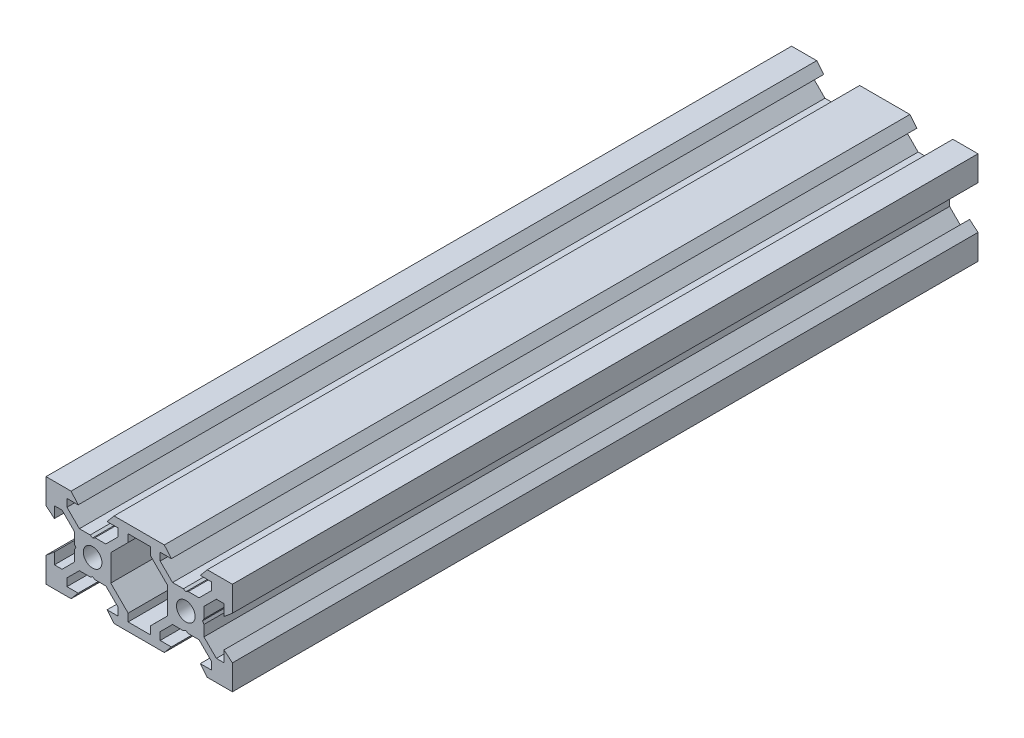
SolidWorks part; units mm, degrees
ref_plane "Front Plane" through (0, 0, 0) normal (0, 0, 1) x (1, 0, 0)
ref_plane "Top Plane" through (0, 0, 0) normal (0, 1, 0) x (1, 0, 0)
ref_plane "Right Plane" through (0, 0, 0) normal (1, 0, 0) x (0, 0, -1)
sketch "Sketch1" plane through (0, 0, 0) normal (0, 0, 1) x (1, 0, 0)
  line L0 (-5.3896, 10) -> (5.3896, 10)
  line L1 (0, 10) -> (0, 4.6104) construction
  line L2 (-6.1, -2.8393) -> (-2.3769, -6.5562)
  line L3 (5.3896, -10) -> (-5.3896, -10) construction
  line L5 (-6.1, 2.8393) -> (-6.1, -2.8393)
  line L6 (-4.5, 8.2) -> (-4.5, 6.5562)
  line L7 (2.3832, 6.5562) -> (2.3832, 8.2)
  line L9 (-6.1, 2.8393) -> (-2.3832, 6.5562)
  line L10 (-4.5, 6.5562) -> (-7.1607, 3.9)
  line L11 (-2.3832, 6.5562) -> (-2.3832, 8.2)
  line L12 (-5.3896, 10) -> (-6.9, 8.2)
  line L13 (6.1, 2.8393) -> (2.3832, 6.5562)
  line L14 (-6.9, 8.2) -> (-4.5, 8.2)
  line L15 (-16.5562, 5.5) -> (-18.2, 5.5)
  line L16 (0, 0) -> (6.1, 0) construction
  line L17 (-6.9, -8.2) -> (-4.5, -8.2)
  line L18 (-2.3769, -6.5562) -> (-2.3769, -8.2)
  line L19 (-5.3896, -10) -> (-6.9, -8.2)
  line L20 (2.3769, -6.5562) -> (2.3769, -8.2)
  line L21 (-9.4804, -3.9002) -> (-10, -3.6002)
  line L22 (-9.4804, 3.8998) -> (-10, 3.5998)
  line L23 (6.1, -2.8393) -> (2.3769, -6.5562)
  line L24 (-2.3769, -8.2) -> (2.3769, -8.2)
  line L25 (-2.3832, 8.2) -> (2.3832, 8.2)
  line L26 (-9.4804, 3.8998) -> (-7.1607, 3.9)
  line L27 (-5.3896, -10) -> (5.3896, -10)
  line L28 (-9.4804, -3.9002) -> (-7.1604, -3.9002)
  line L29 (-4.5, -6.5562) -> (-7.1607, -3.9)
  line L30 (-20, 10) -> (20, 10) construction
  line L32 (6.1, 2.8393) -> (6.1, -2.8393)
  line L33 (-4.5, -8.2) -> (-4.5, -6.5562)
  line L34 (-16.5562, -5.5) -> (-18.2, -5.5)
  line L36 (-10, 0) -> (-10, 8.2) construction
  line L37 (-20, -10) -> (-14.6104, -10) construction
  line L38 (-20, -10) -> (-20, -4.6104) construction
  line L39 (-20, 10) -> (-20, 4.6104) construction
  line L40 (-20, 10) -> (-14.6104, 10) construction
  line L41 (-20, -10) -> (-20, -4.6104)
  line L42 (-15.5, -8.2) -> (-15.5, -6.5562)
  line L43 (-20, -10) -> (-14.6104, -10)
  line L44 (7.1519, 3.8998) -> (9.4804, 3.8998)
  line L45 (-16.5562, -5.5) -> (-13.9, -2.8393)
  line L46 (-15.5, -6.5562) -> (-12.8393, -3.9)
  line L47 (-12.8393, -3.9) -> (-10.5196, -3.9002)
  line L48 (-13.9, -2.8393) -> (-13.9, -0.5196)
  line L49 (-12.8393, 3.9) -> (-10.5196, 3.8998)
  line L50 (-13.9, 0.5196) -> (-13.9, 2.8393)
  line L51 (-13.9, 0.5196) -> (-13.6, 0)
  line L52 (-13.6, 0) -> (-13.9, -0.5196)
  line L53 (-10.5196, 3.8998) -> (-10, 3.5998)
  line L54 (-10.5196, -3.9002) -> (-10, -3.6002)
  line L55 (-20, -4.6104) -> (-18.2, -3.1)
  line L56 (-14.6104, -10) -> (-13.1, -8.2)
  line L57 (-18.2, -3.1) -> (-18.2, -5.5)
  line L58 (-13.1, -8.2) -> (-15.5, -8.2)
  line L59 (-20, -10) -> (20, -10) construction
  line L60 (-20, -10) -> (-20, 10) construction
  line L61 (-13.1, 8.2) -> (-15.5, 8.2)
  line L62 (-18.2, 3.1) -> (-18.2, 5.5)
  line L63 (-14.6104, 10) -> (-13.1, 8.2)
  line L64 (-20, 4.6104) -> (-18.2, 3.1)
  line L65 (-15.5, 6.5562) -> (-12.8393, 3.9)
  line L66 (-16.5562, 5.5) -> (-13.9, 2.8393)
  line L67 (-20, 10) -> (-20, 4.6104)
  line L68 (-20, 10) -> (-14.6104, 10)
  line L69 (-15.5, 8.2) -> (-15.5, 6.5562)
  line L70 (4.5, 6.5562) -> (7.1519, 3.8998)
  line L71 (15.5, 6.5562) -> (12.8481, 3.8998)
  line L72 (0, -10) -> (0, 10) construction
  line L73 (-20, -10) -> (0, 10) construction
  line L74 (10.5196, 3.8998) -> (12.8481, 3.8998)
  line L75 (12.8393, -3.9) -> (10.5192, -3.9)
  line L76 (20, -10) -> (0, 10) construction
  line L77 (20, -10) -> (20, 10) construction
  line L78 (20, 10) -> (14.6104, 10) construction
  line L79 (20, 10) -> (20, 4.6104) construction
  line L80 (20, -10) -> (20, -4.6104) construction
  line L81 (20, -10) -> (14.6104, -10) construction
  line L82 (10, 0) -> (10, 8.2) construction
  line L83 (20, 10) -> (20, 4.6104)
  line L84 (15.5, 8.2) -> (15.5, 6.5562)
  line L85 (20, 10) -> (14.6104, 10)
  line L87 (16.5562, 5.5) -> (13.9, 2.8393)
  line L89 (20, 4.6104) -> (18.2, 3.1)
  line L90 (14.6104, 10) -> (13.1, 8.2)
  line L91 (18.2, 3.1) -> (18.2, 5.5)
  line L92 (13.1, 8.2) -> (15.5, 8.2)
  line L93 (13.1, -8.2) -> (15.5, -8.2)
  line L94 (18.2, -3.1) -> (18.2, -5.5)
  line L95 (14.6104, -10) -> (13.1, -8.2)
  line L96 (20, -4.6104) -> (18.2, -3.1)
  line L97 (10.5196, -3.9002) -> (10, -3.6002)
  line L98 (10.5196, 3.8998) -> (10, 3.5998)
  line L99 (13.6, 0) -> (13.9, -0.5196)
  line L100 (13.9, 0.5196) -> (13.6, 0)
  line L101 (13.9, 0.5196) -> (13.9, 2.8393)
  line L102 (9.4808, -3.9) -> (7.1607, -3.9)
  line L103 (13.9, -2.8393) -> (13.9, -0.5196)
  line L105 (15.5, -6.5562) -> (12.8393, -3.9)
  line L106 (16.5562, -5.5) -> (13.9, -2.8393)
  line L107 (20, -10) -> (20, -4.6104)
  line L108 (20, -10) -> (14.6104, -10)
  line L109 (15.5, -8.2) -> (15.5, -6.5562)
  line L111 (16.5562, -5.5) -> (18.2, -5.5)
  line L112 (4.5, -8.2) -> (4.5, -6.5562)
  line L114 (4.5, -6.5562) -> (7.1607, -3.9)
  line L121 (9.4804, 3.8998) -> (10, 3.5998)
  line L122 (9.4804, -3.9002) -> (10, -3.6002)
  line L124 (5.3896, -10) -> (6.9, -8.2)
  line L126 (6.9, -8.2) -> (4.5, -8.2)
  line L128 (16.5562, 5.5) -> (18.2, 5.5)
  line L129 (6.9, 8.2) -> (4.5, 8.2)
  line L131 (5.3896, 10) -> (6.9, 8.2)
  line L135 (4.5, 8.2) -> (4.5, 6.5562)
  circle A0 centre (-10, 0) radius 2
  circle A1 centre (10, 0) radius 2
  dimension "D14" = 4
  dimension "D1" = 20
  dimension "D2" = 5.3896
  dimension "D3" = 1.8
  dimension "D4" = 1.5104
  dimension "D5" = 4.5
  dimension "D6" = 5.5
  dimension "D7" = 120
  dimension "D8" = 0.3
  dimension "D9" = 2.3197
  dimension "D10" = 7.8
  dimension "D11" = 20
  dimension "D12" = 1.5
  dimension "D13" = 2.6607
  dimension "D15" = 50
  dimension "D16" = 1.5
  dimension "D17" = 1.8
  dimension "D18" = 16.4
  dimension "D19" = 2.3832
  dimension "D20" = 45
extrude "Boss-Extrude1" add sketch "Sketch1" along normal blind 160
